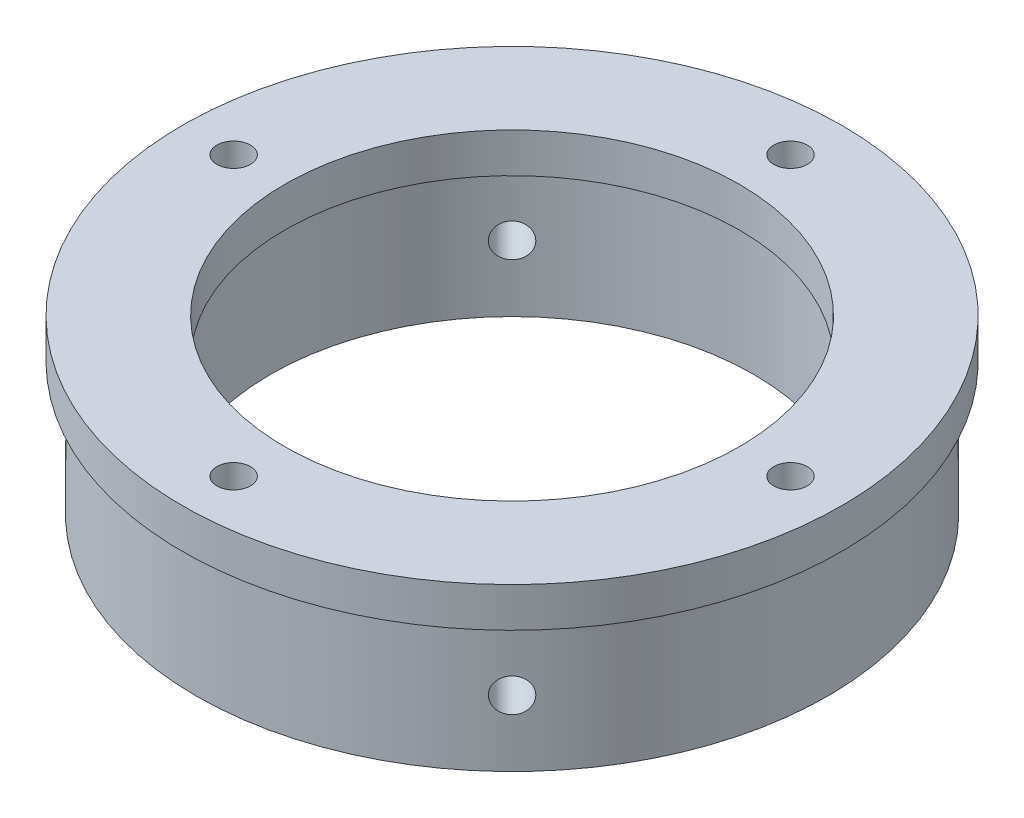
SolidWorks part; units mm, degrees
material "6061-T6 (SS)"
ref_plane "Front Plane" through (0, 0, 0) normal (0, 0, 1) x (1, 0, 0)
ref_plane "Top Plane" through (0, 0, 0) normal (0, 1, 0) x (1, 0, 0)
ref_plane "Right Plane" through (0, 0, 0) normal (1, 0, 0) x (0, 0, -1)
sketch "Sketch1" plane through (0, 0, 0) normal (0, 1, 0) x (1, 0, 0)
  circle A0 centre (0, 0) radius 37.973
  circle A1 centre (0, 0) radius 29.0322
  dimension "D1" = 58.0644
  dimension "D2" = 75.946
extrude "Boss-Extrude1" add sketch "Sketch1" along normal blind 15.875
sketch "Sketch3" plane through (0, 15.875, 0) normal (0, 1, 0) x (1, 0, 0)
  circle A0 centre (0, 0) radius 39.624
  circle A1 centre (0, 0) radius 27.3304
  dimension "D1" = 54.6608
  dimension "D2" = 79.248
extrude "Boss-Extrude2" add sketch "Sketch3" along normal blind 4.7625
sketch "Sketch4" plane through (0, 20.6375, 0) normal (0, 1, 0) x (1, 0, 0)
  line L1 (27.3304, 0) -> (39.624, 0) construction
  circle A0 centre (0, 0) radius 27.3304 construction
  circle A1 centre (0, 0) radius 39.624 construction
  circle A2 centre (33.4772, 0) radius 2.0193
  dimension "D1" = 4.0386
extrude "Cut-Extrude1" cut sketch "Sketch4" against normal blind 38.5445
ref_plane "45 Degree plane " through (0, 0, 0) normal (0.7071, 0, -0.7071) x (-0.7071, 0, -0.7071)
pattern_circular "CirPattern2" count 4 over 360 about axis through (0, 0, 0) along (0, 1, 0) of "Cut-Extrude1"
sketch "Sketch5" plane through (0, 0, 0) normal (0.7071, 0, -0.7071) x (-0.7071, 0, -0.7071)
  line L0 (0, 0) -> (0, 15.875)
  line L1 (-37.973, 15.875) -> (37.973, 15.875) construction
  circle A0 centre (0, 7.9375) radius 2.0193
  dimension "D1" = 4.0386
extrude "Cut-Extrude2" cut sketch "Sketch5" against normal blind 52.2605 contours A0
pattern_circular "CirPattern3" count 4 over 360 about axis through (0, 15.875, 0) along (0, -1, 0) of "Cut-Extrude2"
